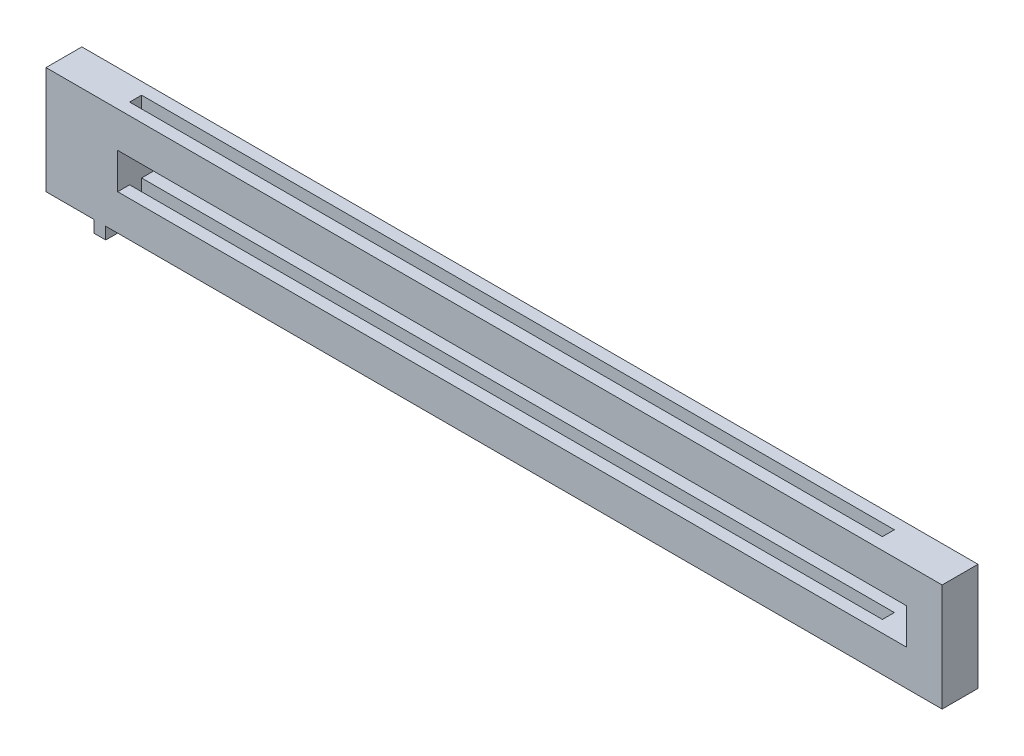
SolidWorks part; units mm, degrees
ref_plane "Front Plane" through (0, 0, 0) normal (0, 0, 1) x (1, 0, 0)
ref_plane "Top Plane" through (0, 0, 0) normal (0, 1, 0) x (1, 0, 0)
ref_plane "Right Plane" through (0, 0, 0) normal (1, 0, 0) x (0, 0, -1)
sketch "Sketch1" plane through (0, 0, 0) normal (0, 0, 1) x (1, 0, 0)
  line L0 (-60, 7.5) -> (60, -7.5) construction
  line L1 (-60, 7.5) -> (60, 7.5)
  line L2 (-60, 7.5) -> (-60, -7.5)
  line L3 (-60, -7.5) -> (60, -7.5)
  line L4 (60, 7.5) -> (60, -7.5)
  line L5 (60, 7.5) -> (-60, -7.5) construction
  line L7 (-55, 2.5) -> (55, 2.5)
  line L8 (-55, 2.5) -> (-55, -2.5)
  line L9 (-55, -2.5) -> (55, -2.5)
  line L10 (55, 2.5) -> (55, -2.5)
  point P4 (0, 0)
  dimension "D1" = 120
  dimension "D2" = 15
  dimension "D3" = 5
  dimension "D4" = 5
  dimension "D5" = 5
  dimension "D6" = 5
extrude "Slider Main Body" add sketch "Sketch1" along normal blind 5
sketch "Sketch2" plane through (0, -7.5, 0) normal (0, -1, 0) x (1, 0, 0)
  line L0 (-55, 5) -> (-55, 0) construction
  line L1 (-55, 5) -> (-55, 0)
  line L3 (-58.3333, 5) -> (-56.6667, 5)
  line L4 (-60, 0) -> (60, 0)
  line L5 (60, 0) -> (60, 5)
  line L6 (60, 5) -> (-60, 5)
  line L7 (-60, 5) -> (-60, 0)
  line L8 (-60, 0) -> (60, 0)
  line L9 (60, 0) -> (60, 5)
  line L10 (60, 5) -> (-60, 5)
  line L11 (-60, 5) -> (-60, 0)
  line L12 (-58.3333, 5) -> (-58.3333, 0)
  line L13 (-58.3333, 0) -> (-56.6667, 0)
  line L14 (-56.6667, 5) -> (-56.6667, 0)
  line M10 (60, 5) -> (-60, 5)
  dimension "D2" = 1.6667
  dimension "D3" = 1.6667
extrude "Track Slider" add sketch "Sketch2" along normal blind 1.6667 contours L14 L12 L8 M10
sketch "Sketch3" plane through (0, 0, 5) normal (0, 0, 1) x (1, 0, 0)
  line L0 (-56.6667, -7.5) -> (60, -7.5) construction
  line L1 (-60, 7.5) -> (-65, 7.5)
  line L2 (-60, 7.5) -> (-60, -7.5)
  line L3 (-60, -7.5) -> (-65, -7.5)
  line L4 (-65, 7.5) -> (-65, -7.5)
  dimension "D1" = 5
extrude "Handle" add sketch "Sketch3" against normal up to surface (5 mm away) up to face at (-28.75, -4.1667, 0)
sketch "Sketch5" plane through (0, -7.5, 0) normal (0, -1, 0) x (1, 0, 0)
  line L0 (55, 5) -> (55, 0) construction
  line L1 (-55, 5) -> (-55, 0) construction
  line L2 (55, 5) -> (55, 0)
  line L3 (-55, 5) -> (-55, 0)
  line L4 (60, 5) -> (-56.6667, 5)
  line L5 (-56.6667, 5) -> (-56.6667, 0)
  line L6 (-56.6667, 0) -> (60, 0)
  line L7 (60, 0) -> (60, 5)
  line L8 (55, 5) -> (-55, 5)
  line L10 (-55, 0) -> (55, 0)
  line L12 (50, 5) -> (50, 0)
  line L14 (-55, 3.3333) -> (50, 3.3333)
  line L15 (-55, 3.3333) -> (-55, 1.6667)
  line L16 (-55, 1.6667) -> (50, 1.6667)
  line L17 (50, 3.3333) -> (50, 1.6667)
  dimension "D3" = 1.6667
  dimension "D2" = 5
  dimension "D4" = 1.6667
extrude "Cut-Extrude1" cut sketch "Sketch5" against normal through all contours L3 L16 L12 L14
equation "\"Frame Side Length\"= \"Useful Tray Size\" + \"Universal Bar Height\" * 3"
equation "\"Universal Bar Height\"= 5mm"
equation "\"D1@Sketch1\"=\"Frame Side Length\"+\"Universal Bar Height\""
equation "\"D2@Sketch1\"=\"Universal Bar Height\"*3"
equation "\"D3@Sketch1\"=\"Universal Bar Height\""
equation "\"D4@Sketch1\"=\"Universal Bar Height\""
equation "\"D5@Sketch1\"=\"Universal Bar Height\""
equation "\"D6@Sketch1\"=\"Universal Bar Height\""
equation "\"D1@Slider Main Body\" = \"Universal Bar Height\""
equation "\"D2@Sketch2\"=\"Universal Bar Height\"/3"
equation "\"D3@Sketch2\"=\"Universal Bar Height\"/3"
equation "\"D1@Track Slider\" = \"Universal Bar Height\" / 3"
equation "\"Useful Tray Size\"= 100mm"
equation "\"D2@Sketch5\"=\"Universal Bar Height\""
equation "\"D3@Sketch5\"=\"Universal Bar Height\"/3"
equation "\"D4@Sketch5\"=\"Universal Bar Height\"/3"
